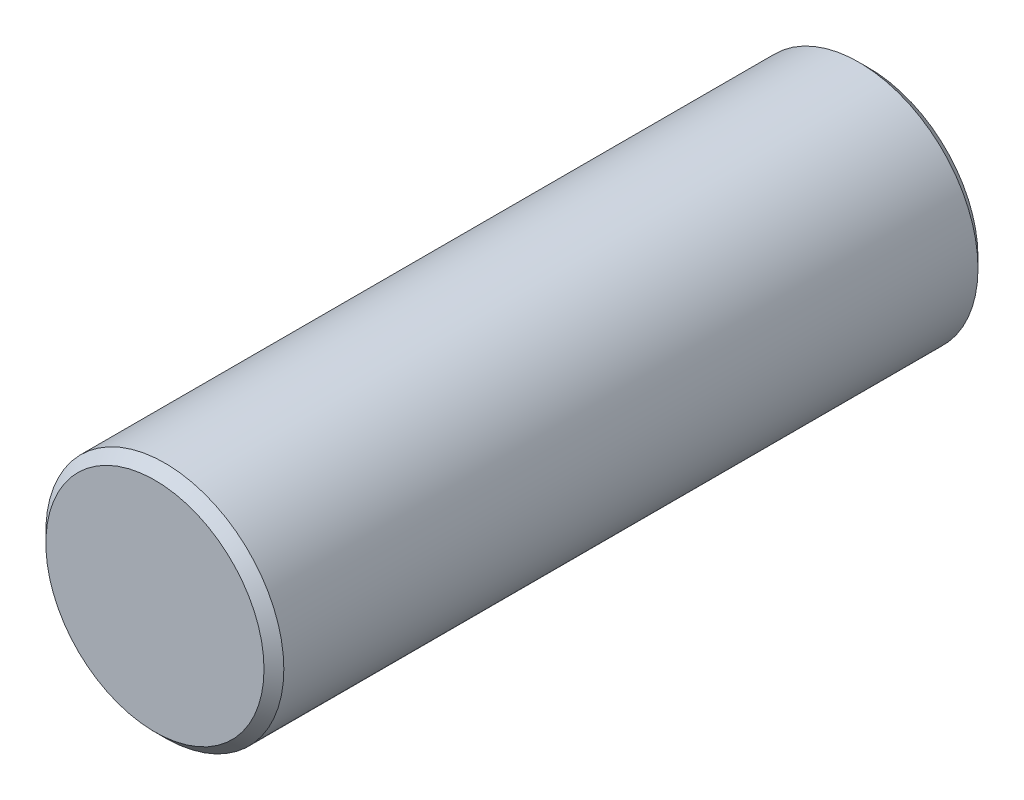
SolidWorks part; units mm, degrees
material "AISI 1045 Steel, cold drawn"
ref_plane "Front Plane" through (0, 0, 0) normal (0, 0, 1) x (1, 0, 0)
ref_plane "Top Plane" through (0, 0, 0) normal (0, 1, 0) x (1, 0, 0)
ref_plane "Right Plane" through (0, 0, 0) normal (1, 0, 0) x (0, 0, -1)
sketch "Sketch1" plane through (0, 0, 0) normal (0, 0, 1) x (1, 0, 0)
  circle A0 centre (0, 0) radius 1.5
  dimension "D1" = 3
extrude "Boss-Extrude1" add sketch "Sketch1" along normal mid plane 9
chamfer "Chamfer1" distance 0.125 angle 45 2 edges at (1.5, 0, -4.5) (1.5, 0, 4.5)
